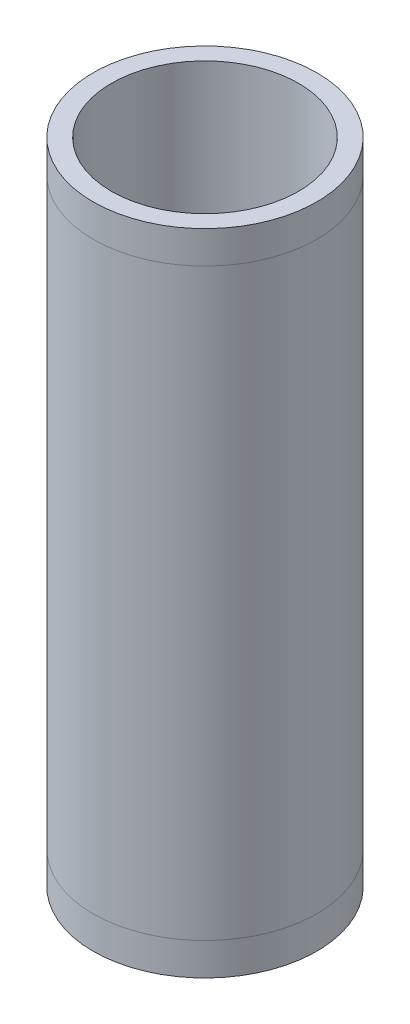
SolidWorks part; units mm, degrees
material "PVC Rigid"
ref_plane "Front Plane" through (0, 0, 0) normal (0, 0, 1) x (1, 0, 0)
ref_plane "Top Plane" through (0, 0, 0) normal (0, 1, 0) x (1, 0, 0)
ref_plane "Right Plane" through (0, 0, 0) normal (1, 0, 0) x (0, 0, -1)
sketch "Sketch1" plane through (0, 0, 0) normal (0, 1, 0) x (1, 0, 0)
  circle A0 centre (0, 0) radius 20.193
  circle A1 centre (0, 0) radius 24.13
  dimension "D1" = 48.26
  dimension "D2" = 40.386
extrude "Boss-Extrude1" add sketch "Sketch1" along normal blind 140
ref_plane "Plane2" through (0, 7, 0) normal (0, 1, 0) x (1, 0, 0)
ref_plane "Plane1" through (0, 133, 0) normal (0, 1, 0) x (1, 0, 0)
split line "Split Line1"
split line "Split Line2"
